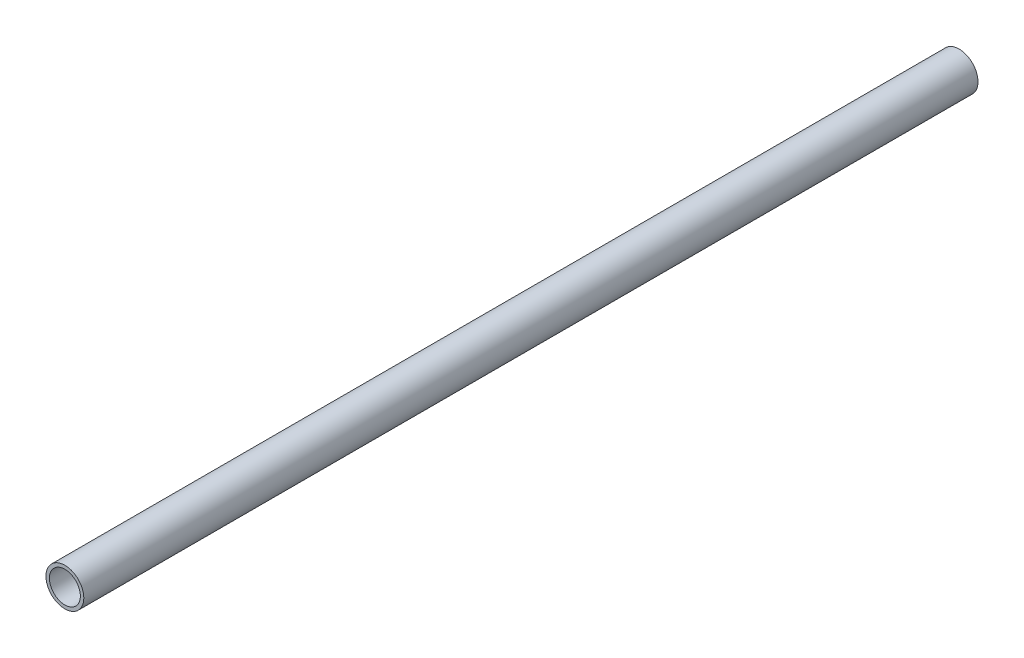
SolidWorks part; units mm, degrees
material "Alliage 1060"
ref_plane "Plan de face" through (0, 0, 0) normal (0, 0, 1) x (1, 0, 0)
ref_plane "Plan de dessus" through (0, 0, 0) normal (0, 1, 0) x (1, 0, 0)
ref_plane "Plan de droite" through (0, 0, 0) normal (1, 0, 0) x (0, 0, -1)
sketch "Esquisse1" plane through (0, 0, 0) normal (0, 0, 1) x (1, 0, 0)
  circle A0 centre (0, 0) radius 11
  circle A1 centre (0, 0) radius 9
  dimension "D1" = 22
  dimension "D2" = 2
extrude "Boss.-Extru.1" add sketch "Esquisse1" along normal blind 520
